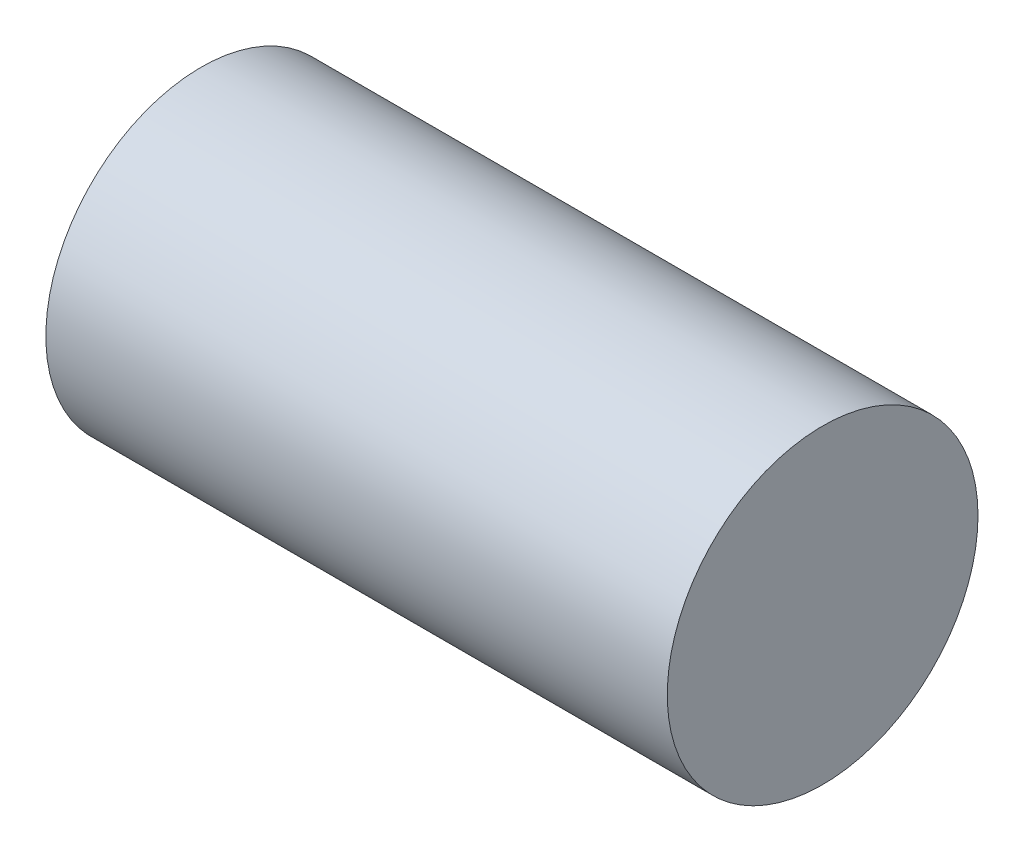
SolidWorks part; units mm, degrees
ref_plane "Front Plane" through (0, 0, 0) normal (0, 0, 1) x (1, 0, 0)
ref_plane "Top Plane" through (0, 0, 0) normal (0, 1, 0) x (1, 0, 0)
ref_plane "Right Plane" through (0, 0, 0) normal (1, 0, 0) x (0, 0, -1)
sketch "Sketch2" plane through (0, 0, 0) normal (1, 0, 0) x (0, 0, -1)
  circle A0 centre (0, 0) radius 6.35
  dimension "D1" = 12.7
extrude "Boss-Extrude1" add sketch "Sketch2" along normal blind 25.4
